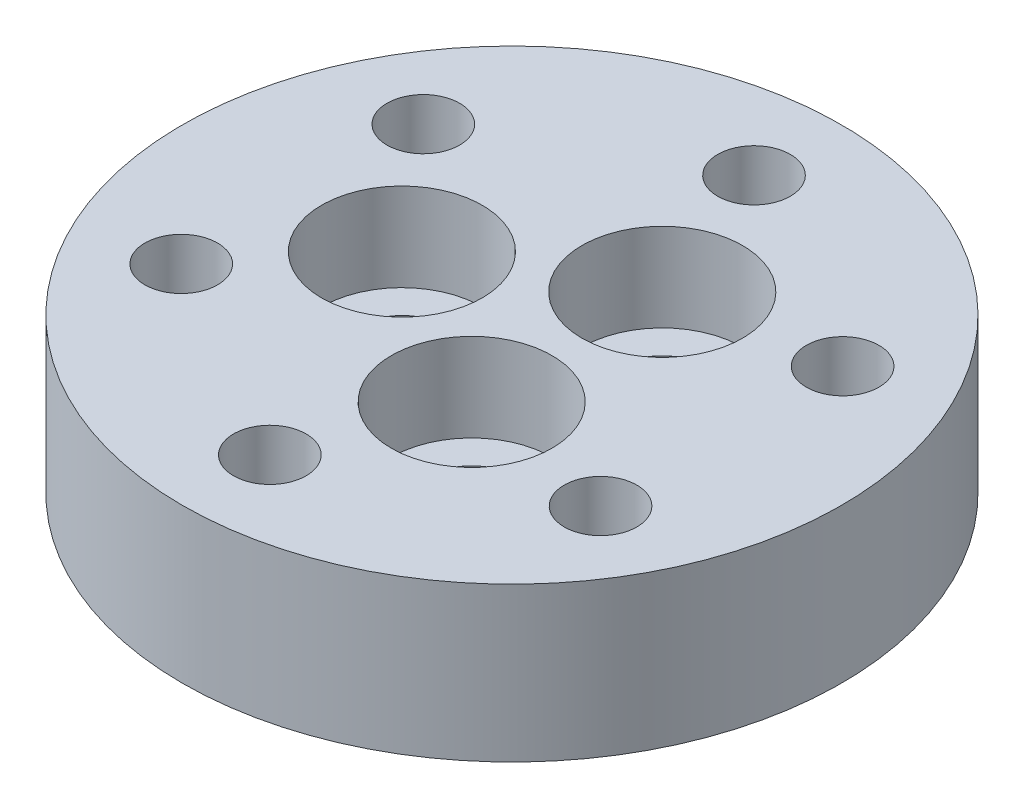
SolidWorks part; units mm, degrees
ref_plane "前视基准面" through (0, 0, 0) normal (0, 0, 1) x (1, 0, 0)
ref_plane "上视基准面" through (0, 0, 0) normal (0, 1, 0) x (1, 0, 0)
ref_plane "右视基准面" through (0, 0, 0) normal (1, 0, 0) x (0, 0, -1)
other "Configuration Table"
sketch "草图1" plane through (0, 0, 0) normal (0, 1, 0) x (1, 0, 0)
  circle A0 centre (0, 0) radius 14.975
  dimension "D1" = 29.95
extrude "凸台-拉伸1" add sketch "草图1" along normal blind 7
sketch "草图2" plane through (0, 7, 0) normal (0, 1, 0) x (1, 0, 0)
  circle A0 centre (0, 0) radius 5 construction
  circle A1 centre (-5, 0) radius 2.1
  circle A2 centre (2.5, 4.3301) radius 2.1
  circle A3 centre (2.5, -4.3301) radius 2.1
  point P17 (0, 0)
  dimension "D1" = 10
  dimension "D2" = 4.2
  dimension "D3" = 3
extrude "切除-拉伸1" cut sketch "草图2" against normal blind 10
sketch "草图3" plane through (0, 7, 0) normal (0, 1, 0) x (1, 0, 0)
  circle A0 centre (0, 0) radius 11 construction
  circle A1 centre (0, 11) radius 1.65
  circle A2 centre (9.5263, 5.5) radius 1.65
  circle A3 centre (9.5263, -5.5) radius 1.65
  circle A4 centre (0, -11) radius 1.65
  circle A5 centre (-9.5263, -5.5) radius 1.65
  circle A6 centre (-9.5263, 5.5) radius 1.65
  point P17 (0, 0)
  dimension "D1" = 22
  dimension "D2" = 3.3
  dimension "D3" = 6
extrude "切除-拉伸2" cut sketch "草图3" against normal blind 10
sketch "草图5" plane through (0, 7, 0) normal (0, 1, 0) x (1, 0, 0)
  circle A0 centre (-5, 0) radius 3.65
  circle A1 centre (2.5, 4.3301) radius 3.65
  circle A2 centre (2.5, -4.3301) radius 3.65
  dimension "D1" = 7.3
  dimension "D2" = 7.3
  dimension "D3" = 7.3
extrude "切除-拉伸3" cut sketch "草图5" against normal blind 4
